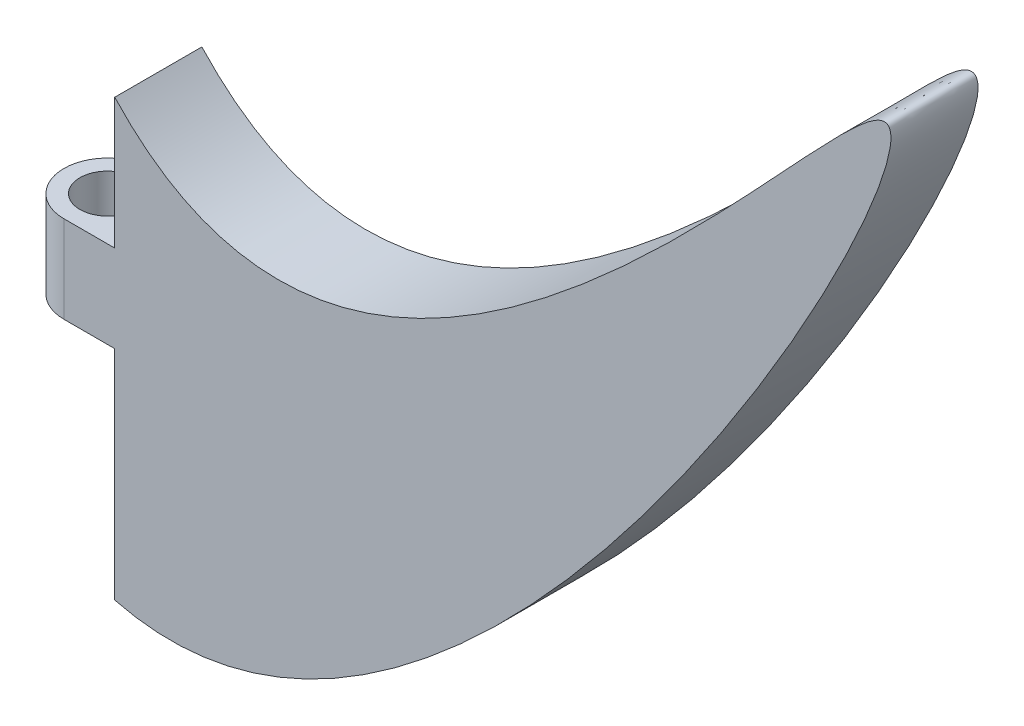
SolidWorks part; units mm, degrees
ref_plane "Alzado" through (0, 0, 0) normal (0, 0, 1) x (1, 0, 0)
ref_plane "Planta" through (0, 0, 0) normal (0, 1, 0) x (1, 0, 0)
ref_plane "Vista lateral" through (0, 0, 0) normal (1, 0, 0) x (0, 0, -1)
sketch "Croquis1" plane through (0, 0, 0) normal (0, 0, 1) x (1, 0, 0)
  line L0 (0, 0) -> (0, 30)
  spline S0 degree 3 poles (0, 0) (25.7274, -6.6185) (85.0033, 107.7815) (18.5263, 9.9948) (0, 30) knots 0 0 0 0 0.555968 1 1 1 1
  dimension "D1" = 30
extrude "Saliente-Extruir1" add sketch "Croquis1" along normal blind 6
sketch "Croquis2" plane through (0, 0, 0) normal (0, 1, 0) x (1, 0, 0)
  line L1 (0, 0) -> (-3.5, 0)
  line L2 (0, 0) -> (0, -6)
  line L3 (0, -6) -> (-3.5, -6)
  arc A0 (-3.5, 0) -> (-3.5, -6) centre (-3.5, -3) ccw
  dimension "D1" = 6
  dimension "D2" = 3.5
extrude "Saliente-Extruir2" add sketch "Croquis2" along normal blind 6 from offset 15
sketch "Croquis3" plane through (0, 21, 0) normal (0, 1, 0) x (1, 0, 0)
  line L0 (-3.5, -6) -> (0, -6) construction
  circle A0 centre (-3.5, -3) radius 1.9
  arc A1 (-3.5, 0) -> (-3.5, -6) centre (-3.5, -3) ccw construction
  point P5 (-6.5, -3)
  dimension "D1" = 3.8
  dimension "D2" = 3
  dimension "D3" = 3
extrude "Cortar-Extruir1" cut sketch "Croquis3" against normal blind 6
